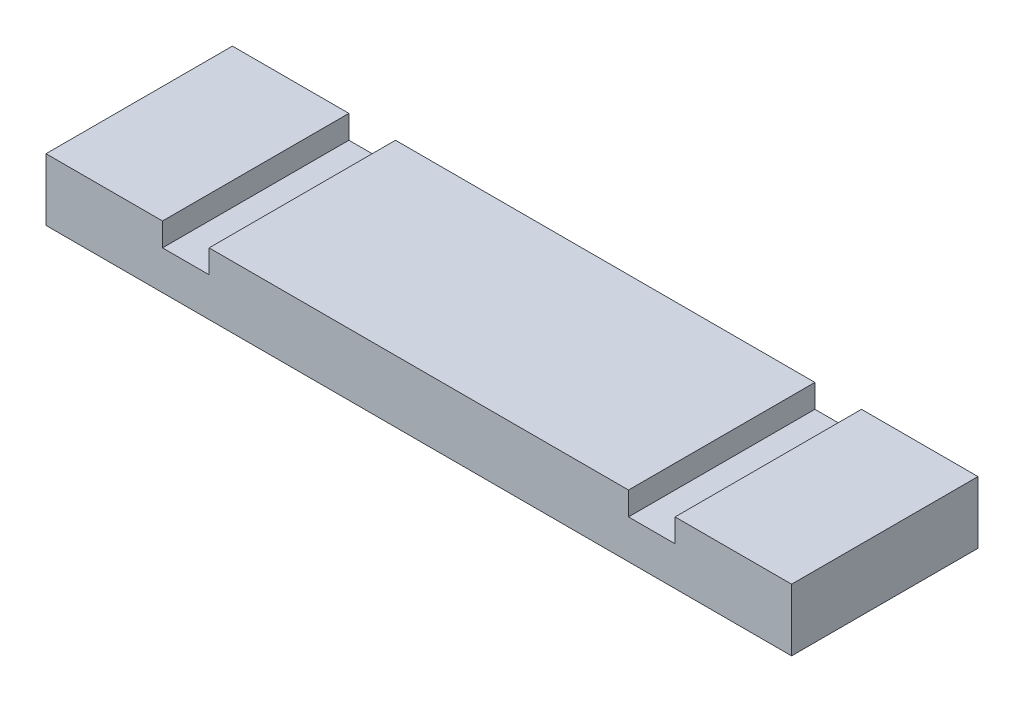
SolidWorks part; units mm, degrees
ref_plane "Front Plane" through (0, 0, 0) normal (0, 0, 1) x (1, 0, 0)
ref_plane "Top Plane" through (0, 0, 0) normal (0, 1, 0) x (1, 0, 0)
ref_plane "Right Plane" through (0, 0, 0) normal (1, 0, 0) x (0, 0, -1)
sketch "Sketch1" plane through (0, 0, 0) normal (0, 1, 0) x (1, 0, 0)
  line L1 (-24, -6) -> (24, -6)
  line L2 (-24, -6) -> (-24, 6)
  line L3 (-24, 6) -> (24, 6)
  line L4 (24, -6) -> (24, 6)
  line L5 (-24, -6) -> (24, 6) construction
  line L6 (-24, 6) -> (24, -6) construction
  point P0 (0, 0)
  dimension "D1" = 48
  dimension "D2" = 12
extrude "Boss-Extrude1" add sketch "Sketch1" along normal blind 4
sketch "Sketch2" plane through (0, 4, 0) normal (0, 1, 0) x (1, 0, 0)
  line L0 (24, 6) -> (-24, 6) construction
  line L1 (-16.5, 6) -> (-13.5, 6)
  line L2 (-16.5, 6) -> (-16.5, -6)
  line L3 (-16.5, -6) -> (-13.5, -6)
  line L4 (-13.5, 6) -> (-13.5, -6)
  line L5 (-24, -6) -> (24, -6) construction
  line L6 (-24, 6) -> (-24, -6) construction
  line L7 (13.5, 6) -> (16.5, 6)
  line L8 (13.5, 6) -> (13.5, -6)
  line L9 (13.5, -6) -> (16.5, -6)
  line L10 (16.5, 6) -> (16.5, -6)
  line L11 (24, -6) -> (24, 6) construction
  dimension "D1" = 7.5
  dimension "D2" = 3
  dimension "D3" = 7.5
  dimension "D4" = 3
extrude "Cut-Extrude1" cut sketch "Sketch2" against normal blind 1.5
